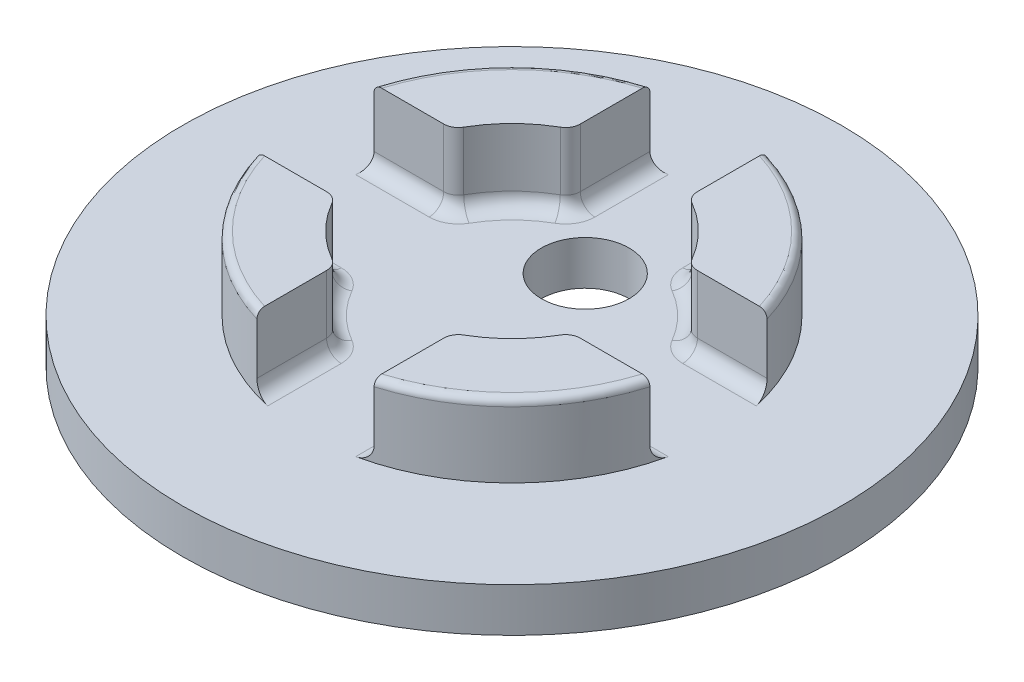
SolidWorks part; units mm, degrees
ref_plane "Front Plane" through (0, 0, 0) normal (0, 0, 1) x (1, 0, 0)
ref_plane "Top Plane" through (0, 0, 0) normal (0, 1, 0) x (1, 0, 0)
ref_plane "Right Plane" through (0, 0, 0) normal (1, 0, 0) x (0, 0, -1)
sketch "Sketch2" plane through (0, 0, 0) normal (0, 1, 0) x (1, 0, 0)
  circle A0 centre (0, 0) radius 22.5
  dimension "D1" = 45
extrude "Boss-Extrude1" add sketch "Sketch2" along normal blind 3
sketch "Sketch3" plane through (0, 3, 0) normal (0, 1, 0) x (1, 0, 0)
  line L1 (-22.5, 4) -> (22.5, 4)
  line L2 (-22.5, 4) -> (-22.5, -4)
  line L3 (-22.5, -4) -> (22.5, -4)
  line L4 (22.5, 4) -> (22.5, -4)
  line L5 (-4, 22.5) -> (4, 22.5)
  line L6 (-4, 22.5) -> (-4, -22.5)
  line L7 (-4, -22.5) -> (4, -22.5)
  line L8 (4, 22.5) -> (4, -22.5)
  circle A0 centre (0, 0) radius 14
  circle A2 centre (0, 0) radius 22.5 construction
  circle A3 centre (0, 0) radius 9
  point P13 (22.5, 0)
  point P15 (0, 22.5)
  dimension "D1" = 28
  dimension "D2" = 5
  dimension "D3" = 8
extrude "Boss-Extrude2" add sketch "Sketch3" along normal blind 5 contours A3 L6 A0 L1 | A3 L1 A0 L8 | A3 L8 A0 L3 | A3 L3 A0 L6
fillet "Fillet1" radius 1 20 edges at (-4, 3, 10.7393) (-4, 3, -10.7393) (-10.7393, 3, 4) (10.7393, 3, 4) (4, 3, 10.7393) (4, 3, -10.7393) (10.7393, 3, -4) (-10.7393, 3, -4) (-6.364, 3, 6.364) (6.364, 3, 6.364) (6.364, 3, -6.364) (-6.364, 3, -6.364) (4, 5.5, 8.0623) (8.0623, 5.5, 4) (4, 5.5, -8.0623) (8.0623, 5.5, -4) (-4, 5.5, -8.0623) (-8.0623, 5.5, -4) (-8.0623, 5.5, 4) (-4, 5.5, 8.0623)
fillet "Fillet2" radius 0.5 4 edges at (9.8995, 8, -9.8995) (-9.8995, 8, -9.8995) (-9.8995, 8, 9.8995) (9.8995, 8, 9.8995)
sketch "Sketch5" plane through (0, 3, 0) normal (0, 1, 0) x (1, 0, 0)
  circle A0 centre (0, 5) radius 3
  point P2 (0, 0)
  dimension "D1" = 6
  dimension "D2" = 5
extrude "Cut-Extrude1" cut sketch "Sketch5" against normal blind 5
